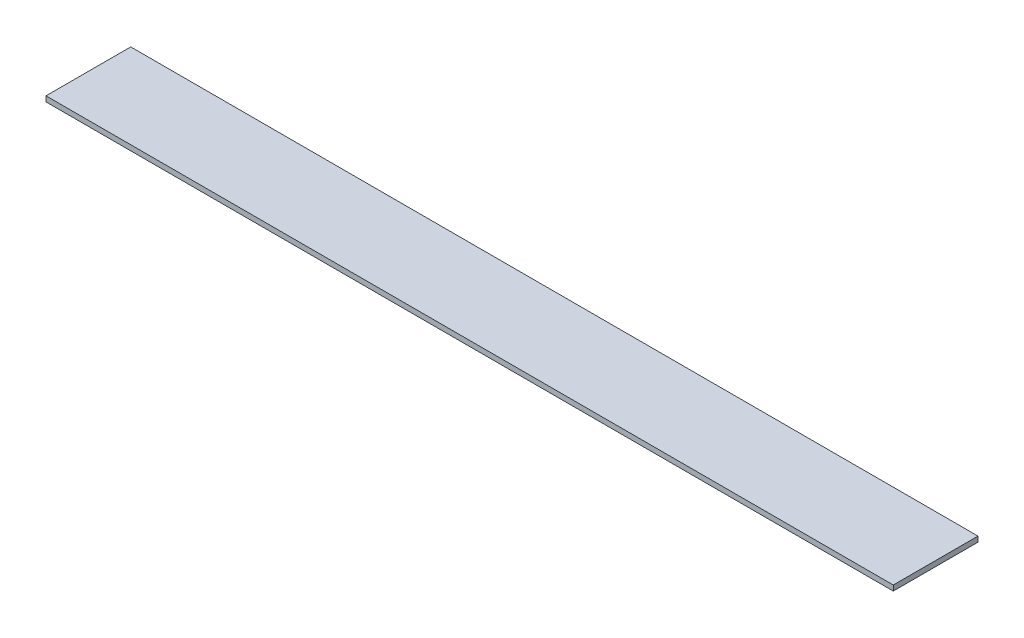
SolidWorks part; units mm, degrees
ref_plane "Front Plane" through (0, 0, 0) normal (0, 0, 1) x (1, 0, 0)
ref_plane "Top Plane" through (0, 0, 0) normal (0, 1, 0) x (1, 0, 0)
ref_plane "Right Plane" through (0, 0, 0) normal (1, 0, 0) x (0, 0, -1)
sketch "Sketch1" plane through (0, 0, 0) normal (0, 1, 0) x (1, 0, 0)
  line L1 (-127, -12.7) -> (127, -12.7)
  line L2 (-127, -12.7) -> (-127, 12.7)
  line L3 (-127, 12.7) -> (127, 12.7)
  line L4 (127, -12.7) -> (127, 12.7)
  line L5 (-127, -12.7) -> (127, 12.7) construction
  line L6 (-127, 12.7) -> (127, -12.7) construction
  point P0 (0, 0)
  dimension "D1" = 254
  dimension "D2" = 25.4
extrude "Boss-Extrude1" add sketch "Sketch1" along normal blind 1.5875
